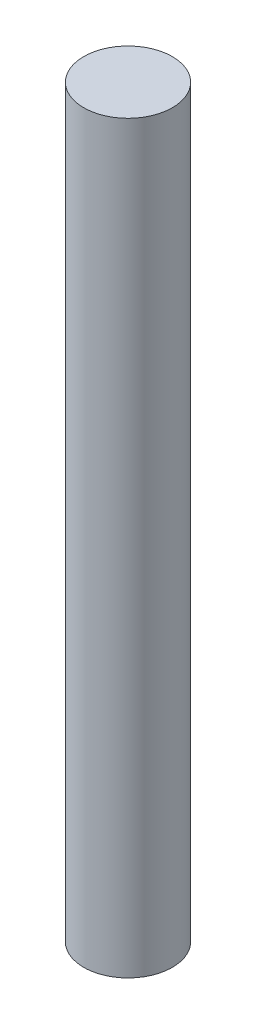
SolidWorks part; units mm, degrees
ref_plane "Front Plane" through (0, 0, 0) normal (0, 0, 1) x (1, 0, 0)
ref_plane "Top Plane" through (0, 0, 0) normal (0, 1, 0) x (1, 0, 0)
ref_plane "Right Plane" through (0, 0, 0) normal (1, 0, 0) x (0, 0, -1)
sketch "Sketch1" plane through (0, 0, 0) normal (0, 1, 0) x (1, 0, 0)
  circle A0 centre (0, 0) radius 5
  dimension "D1" = 10
extrude "Boss-Extrude1" add sketch "Sketch1" along normal blind 84
